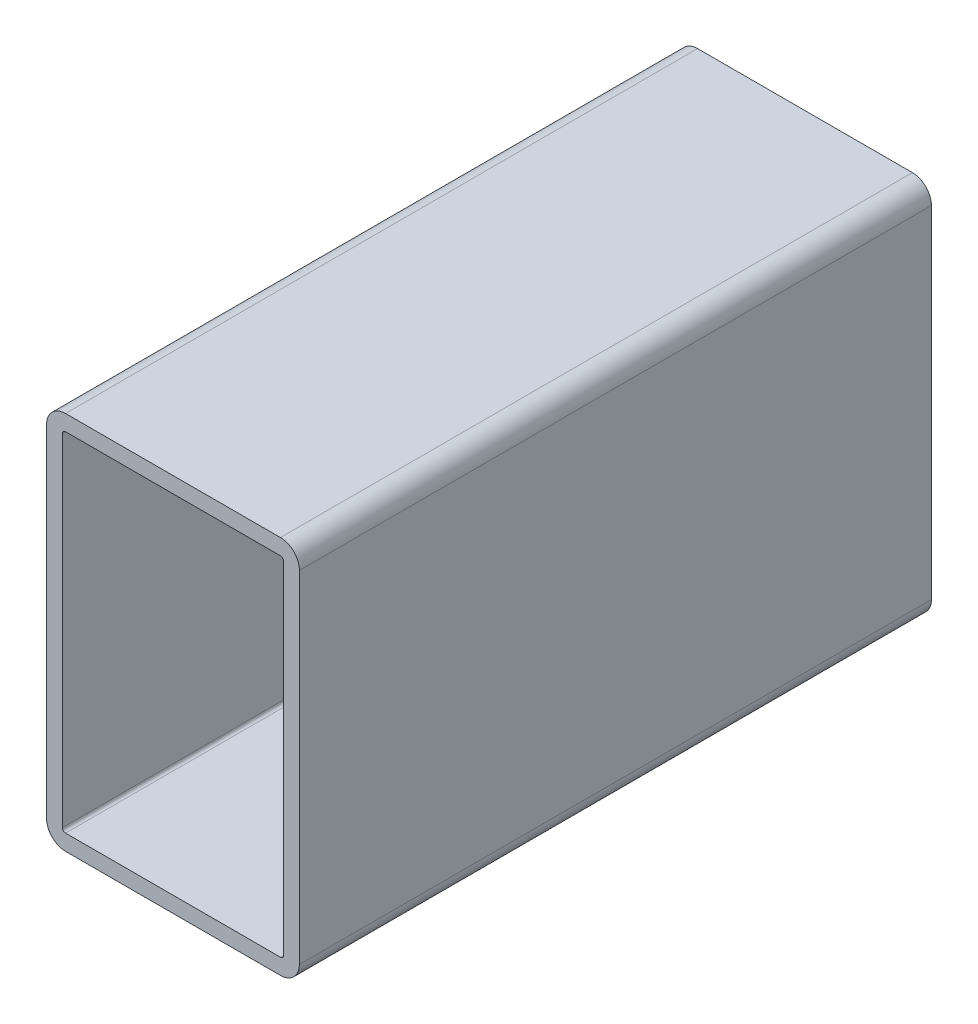
SolidWorks part; units mm, degrees
ref_plane "Front Plane" through (0, 0, 0) normal (0, 0, 1) x (1, 0, 0)
ref_plane "Top Plane" through (0, 0, 0) normal (0, 1, 0) x (1, 0, 0)
ref_plane "Right Plane" through (0, 0, 0) normal (1, 0, 0) x (0, 0, -1)
other "Configuration Table"
sketch "Sketch1" plane through (0, 0, 0) normal (0, 0, 1) x (1, 0, 0)
  line L0 (3, 2.5) -> (37, 2.5)
  line L1 (3, 0) -> (37, 0)
  line L2 (0, 3) -> (0, 57)
  line L3 (3, 60) -> (37, 60)
  line L4 (40, 3) -> (40, 57)
  line L5 (37.5, 3) -> (37.5, 57)
  line L6 (3, 57.5) -> (37, 57.5)
  line L7 (2.5, 3) -> (2.5, 57)
  arc A0 (37, 0) -> (40, 3) centre (37, 3) ccw
  arc A1 (3, 0) -> (0, 3) centre (3, 3) cw
  arc A2 (37, 60) -> (40, 57) centre (37, 57) cw
  arc A3 (0, 57) -> (3, 60) centre (3, 57) cw
  arc A4 (37, 2.5) -> (37.5, 3) centre (37, 3) ccw
  arc A5 (37, 57.5) -> (37.5, 57) centre (37, 57) cw
  arc A6 (2.5, 57) -> (3, 57.5) centre (3, 57) cw
  arc A7 (3, 2.5) -> (2.5, 3) centre (3, 3) cw
  point P7 (40, 0)
  point P10 (0, 0)
  point P13 (40, 60)
  point P16 (0, 60)
  dimension "D3" = 3
  dimension "D1" = 60
  dimension "D2" = 40
  dimension "D4" = 2.5
extrude "Boss-Extrude1" add sketch "Sketch1" along normal blind 100
